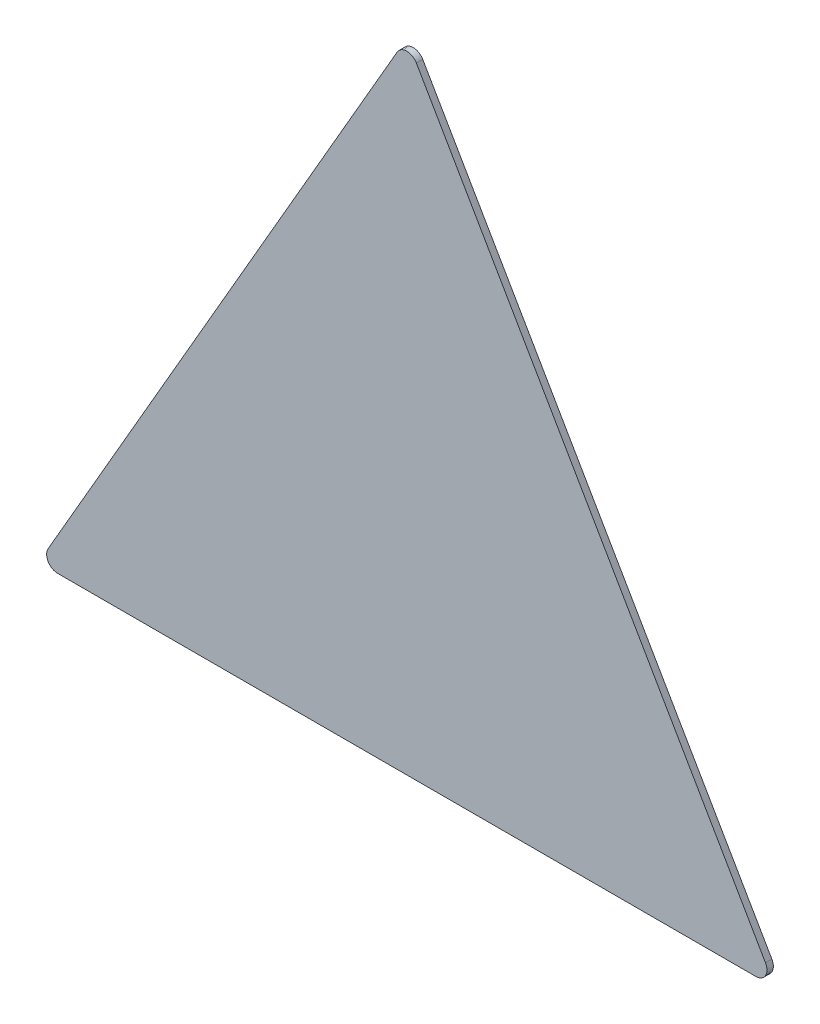
SolidWorks part; units mm, degrees
ref_plane "Plan de face" through (0, 0, 0) normal (0, 0, 1) x (1, 0, 0)
ref_plane "Plan de dessus" through (0, 0, 0) normal (0, 1, 0) x (1, 0, 0)
ref_plane "Plan de droite" through (0, 0, 0) normal (1, 0, 0) x (0, 0, -1)
sketch "Esquisse1" plane through (0, 0, 0) normal (0, 0, 1) x (1, 0, 0)
  line L0 (103.1416, -93.1044) -> (-104.5379, -93.1044)
  line L1 (-107.3957, -88.1544) -> (-3.556, 91.7013)
  line L2 (2.1598, 91.7013) -> (105.997, -88.1501)
  spline S0 degree 5 poles (105.997, -88.1501) (105.9975, -88.151) (105.998, -88.1518) (105.9985, -88.1527) (105.999, -88.1536) (106.0187, -88.1877) (106.038, -88.221) (106.0569, -88.2545) (106.1123, -88.3557) (106.1606, -88.4607) (106.1901, -88.5321) (106.2586, -88.7128) (106.3161, -88.8968) (106.3464, -89.0083) (106.3973, -89.2334) (106.4272, -89.4626) (106.4371, -89.5779) (106.4466, -89.8091) (106.4362, -90.0401) (106.4259, -90.1553) (106.3954, -90.3844) (106.3449, -90.61) (106.3147, -90.7217) (106.2447, -90.9421) (106.1557, -91.1555) (106.1066, -91.2602) (105.9993, -91.465) (105.8744, -91.6596) (105.8078, -91.7541) (105.6665, -91.9371) (105.5097, -92.1071) (105.4276, -92.1886) (105.2566, -92.3442) (105.0726, -92.4841) (104.9776, -92.5501) (104.7821, -92.6735) (104.5765, -92.7797) (104.4715, -92.8283) (104.2586, -92.9152) (104.0391, -92.9822) (103.9284, -93.011) (103.7426, -93.0517) (103.5542, -93.0817) (103.4789, -93.0914) (103.3661, -93.1016) (103.2533, -93.1041) (103.2161, -93.1044) (103.1789, -93.1044) (103.1416, -93.1044) knots 0 0 0 0 0 0 0.000723 0.000723 0.000723 0.000723 0.028555 0.028555 0.028555 0.084219 0.084219 0.084219 0.167714 0.167714 0.167714 0.25121 0.25121 0.25121 0.334705 0.334705 0.334705 0.4182 0.4182 0.4182 0.501696 0.501696 0.501696 0.585191 0.585191 0.585191 0.668686 0.668686 0.668686 0.752182 0.752182 0.752182 0.835677 0.835677 0.835677 0.918283 0.918283 0.918283 0.973057 0.973057 0.973057 1 1 1 1 1 1
  spline S1 degree 5 poles (-104.5379, -93.1044) (-104.5763, -93.1044) (-104.6148, -93.1044) (-104.6532, -93.1041) (-104.7685, -93.1015) (-104.8837, -93.0908) (-104.9603, -93.0807) (-105.151, -93.0496) (-105.3391, -93.0075) (-105.4507, -92.9779) (-105.6711, -92.9094) (-105.8847, -92.8207) (-105.9894, -92.7716) (-106.1944, -92.6643) (-106.3892, -92.5397) (-106.4838, -92.4733) (-106.667, -92.3323) (-106.8372, -92.1757) (-106.9188, -92.0938) (-107.0746, -91.923) (-107.2149, -91.7392) (-107.281, -91.6443) (-107.4048, -91.4489) (-107.5109, -91.2435) (-107.5595, -91.1386) (-107.6473, -90.9247) (-107.7161, -90.7039) (-107.7456, -90.5921) (-107.7949, -90.3662) (-107.8241, -90.1369) (-107.8337, -90.0216) (-107.8428, -89.7906) (-107.832, -89.5594) (-107.8215, -89.4442) (-107.7904, -89.2164) (-107.7386, -88.9927) (-107.7082, -88.8826) (-107.6506, -88.7012) (-107.5824, -88.5231) (-107.5531, -88.453) (-107.5056, -88.3503) (-107.4513, -88.2513) (-107.433, -88.2189) (-107.4144, -88.1867) (-107.3957, -88.1544) knots 0 0 0 0 0 0 0.027852 0.027852 0.027852 0.083556 0.083556 0.083556 0.167112 0.167112 0.167112 0.250667 0.250667 0.250667 0.334223 0.334223 0.334223 0.417779 0.417779 0.417779 0.501335 0.501335 0.501335 0.584891 0.584891 0.584891 0.668446 0.668446 0.668446 0.752002 0.752002 0.752002 0.835558 0.835558 0.835558 0.918224 0.918224 0.918224 0.973038 0.973038 0.973038 1 1 1 1 1 1
  spline S2 degree 5 poles (-3.556, 91.7013) (-3.5368, 91.7346) (-3.5175, 91.7679) (-3.4981, 91.801) (-3.4381, 91.8996) (-3.3713, 91.9939) (-3.3242, 92.0552) (-3.2019, 92.2048) (-3.0714, 92.3467) (-2.99, 92.4286) (-2.8205, 92.5852) (-2.6369, 92.7258) (-2.542, 92.792) (-2.3466, 92.9158) (-2.1413, 93.0223) (-2.0364, 93.071) (-1.8227, 93.1592) (-1.6021, 93.2282) (-1.4903, 93.2579) (-1.2644, 93.3075) (-1.0351, 93.3371) (-0.9199, 93.3469) (-0.6889, 93.3563) (-0.4579, 93.3456) (-0.3427, 93.3351) (-0.1136, 93.3043) (0.112, 93.2534) (0.2236, 93.2231) (0.4439, 93.1528) (0.6571, 93.0634) (0.7617, 93.0141) (0.9664, 92.9066) (1.1611, 92.7816) (1.2557, 92.7149) (1.4374, 92.5741) (1.6052, 92.4174) (1.6854, 92.336) (1.8136, 92.1954) (1.9338, 92.0473) (1.9799, 91.9868) (2.0451, 91.8943) (2.1037, 91.7979) (2.1225, 91.7658) (2.1412, 91.7335) (2.1598, 91.7013) knots 0 0 0 0 0 0 0.027852 0.027852 0.027852 0.083556 0.083556 0.083556 0.167112 0.167112 0.167112 0.250667 0.250667 0.250667 0.334223 0.334223 0.334223 0.417779 0.417779 0.417779 0.501335 0.501335 0.501335 0.584891 0.584891 0.584891 0.668446 0.668446 0.668446 0.752002 0.752002 0.752002 0.835558 0.835558 0.835558 0.918224 0.918224 0.918224 0.973038 0.973038 0.973038 1 1 1 1 1 1
extrude "Boss.-Extru.1" add sketch "Esquisse1" along normal blind 1.9
